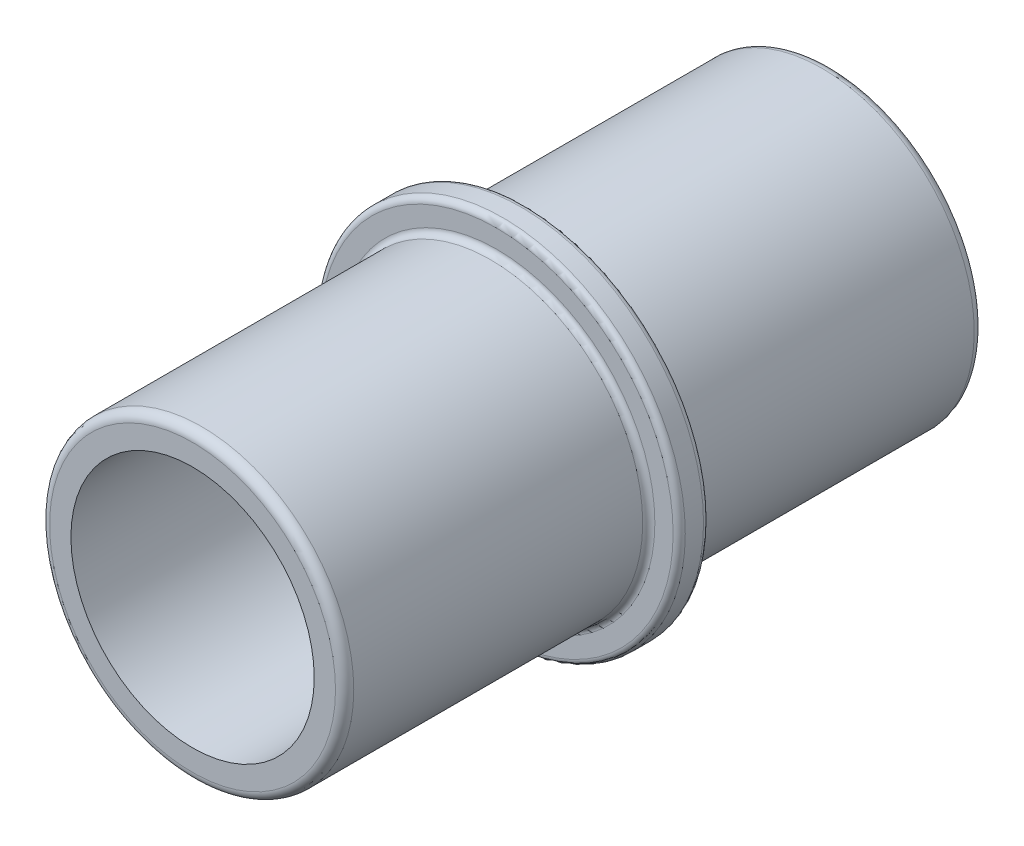
SolidWorks part; units mm, degrees
ref_plane "Front Plane" through (0, 0, 0) normal (0, 0, 1) x (1, 0, 0)
ref_plane "Top Plane" through (0, 0, 0) normal (0, 1, 0) x (1, 0, 0)
ref_plane "Right Plane" through (0, 0, 0) normal (1, 0, 0) x (0, 0, -1)
sketch "Sketch1" plane through (0, 0, 0) normal (0, 0, 1) x (1, 0, 0)
  circle A0 centre (0, 0) radius 0.6
extrude "Boss-Extrude1" add sketch "Sketch1" along normal blind 0.1
sketch "Sketch2" plane through (0, 0, 0.1) normal (0, 0, 1) x (1, 0, 0)
  circle A0 centre (0, 0) radius 0.5
extrude "Boss-Extrude2" add sketch "Sketch2" along normal blind 1
sketch "Sketch4" plane through (0, 0, 0) normal (0, 0, -1) x (-1, 0, 0)
  circle A0 centre (0, 0) radius 0.5
extrude "Boss-Extrude3" add sketch "Sketch4" along normal blind 1
fillet "Fillet1" radius 0.02 1 edges at (0.6, 0, 0)
fillet "Fillet2" radius 0.02 1 edges at (0.6, 0, 0.1)
fillet "Fillet3" radius 0.02 1 edges at (0.5, 0, 0.1)
fillet "Fillet4" radius 0.02 1 edges at (0.5, 0, 0)
fillet "Fillet5" radius 0.03 1 edges at (0.5, 0, 1.1)
fillet "Fillet6" radius 0.03 1 edges at (-0.5, 0, -1)
sketch "Sketch5" plane through (0, 0, 1.1) normal (0, 0, 1) x (1, 0, 0)
  circle A0 centre (0, 0) radius 0.4
extrude "Cut-Extrude1" cut sketch "Sketch5" against normal blind 2.1 contours A0
